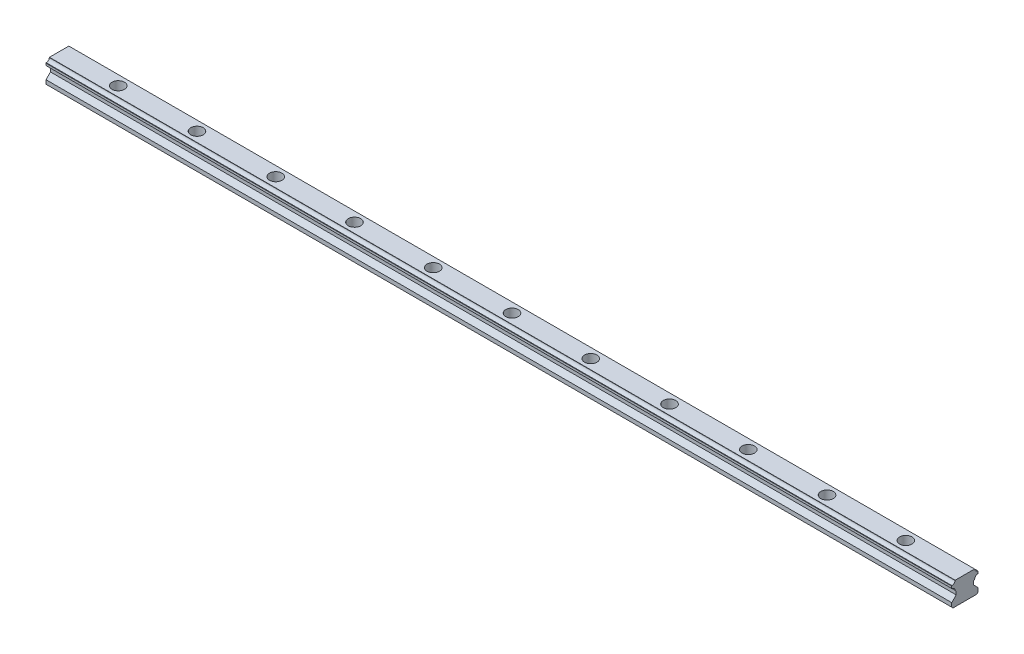
SolidWorks part; units mm, degrees
ref_plane "Спереди" through (0, 0, 0) normal (0, 0, 1) x (1, 0, 0)
ref_plane "Сверху" through (0, 0, 0) normal (0, 1, 0) x (1, 0, 0)
ref_plane "Сбоку" through (0, 0, 0) normal (1, 0, 0) x (0, 0, -1)
sketch "Эскиз1" plane through (0, 0, 0) normal (1, 0, 0) x (0, 0, -1)
  line L0 (-10, 0.9899) -> (-9.0101, 0)
  line L1 (-9.0101, 0) -> (9.0101, 0)
  line L2 (9.0101, 0) -> (10, 0.9899)
  line L3 (10, 0.9899) -> (10, 4)
  line L4 (10, 4) -> (6.6, 7.4)
  line L5 (6.6, 7.4) -> (6.6, 9.9)
  line L6 (6.6, 9.9) -> (7.5, 10.8)
  line L7 (9.8, 13.1) -> (10, 13.3)
  line L8 (10, 13.3) -> (10, 14.9)
  line L9 (10, 14.9) -> (9.8, 15.1)
  line L10 (7.5, 17.4) -> (7.4, 17.5)
  line L11 (7.4, 17.5) -> (-7.4, 17.5)
  line L12 (-7.4, 17.5) -> (-7.5, 17.4)
  line L13 (-9.8, 15.1) -> (-10, 14.9)
  line L14 (-10, 14.9) -> (-10, 13.3)
  line L15 (-10, 13.3) -> (-9.8, 13.1)
  line L16 (-7.5, 10.8) -> (-6.6, 9.9)
  line L17 (-6.6, 9.9) -> (-6.6, 7.4)
  line L18 (-6.6, 7.4) -> (-10, 4)
  line L19 (-10, 4) -> (-10, 0.9899)
  arc A0 (7.5, 10.8) -> (9.8, 13.1) centre (9.8, 10.8) cw
  arc A1 (9.8, 15.1) -> (7.5, 17.4) centre (9.8, 17.4) cw
  arc A2 (-7.5, 17.4) -> (-9.8, 15.1) centre (-9.8, 17.4) cw
  arc A3 (-9.8, 13.1) -> (-7.5, 10.8) centre (-9.8, 10.8) cw
  dimension "D1" = 20
  dimension "D2" = 17.5
extrude "Бобышка-Вытянуть1" add sketch "Эскиз1" against normal mid plane 690
hole_wizard "Цековка M6 для болта с шестигранной головкой класса А ГОСТ 78051" positions "Трехмерный эскиз1" profile "Эскиз4" counterbore size "M6" standard "ГОСТ"
sketch3d "Трехмерный эскиз1"
  line L5 (-345, 17.5, 0) -> (345, 17.5, 0) construction
  line L6 (-345, 17.5, -7.4) -> (-345, 17.5, 7.4) construction
  line L7 (345, 17.5, -7.4) -> (345, 17.5, 7.4) construction
  point P34 (0.3531, 17.5, 0)
  point P49 (0, 17.5, 0)
sketch "Эскиз4" plane through (0, 17.5, 0) normal (1, 0, 0) x (0, 0, 1)
  line L0 (0, 0) -> (0, 19.3016)
  line L1 (0, 19.3016) -> (3, 17.499)
  line L2 (3, 17.499) -> (3, 8.5)
  line L3 (3, 8.5) -> (4.75, 8.5)
  line L4 (4.75, 8.5) -> (4.75, 0)
  line L5 (4.75, 0) -> (0, 0)
  line L10 (0, 19.3016) -> (-3, 17.499) construction
  line L11 (0, -6.35) -> (0, 107.95) construction
  dimension "Диаметр отверстия" = 6
  dimension "Глубина отверстия" = 17.499
  dimension "Диаметр цековки" = 9.5
  dimension "Глубина цековки" = 8.5
  dimension "Угол заточки сверла" = 118
pattern_linear "Линейный массив1" count 6 spacing 60 along (1, 0, 0) of "Цековка M6 для болта с шестигранной головкой класса А ГОСТ 78051"
pattern_linear "Линейный массив2" count 6 spacing 60 along (-1, 0, 0) of "Цековка M6 для болта с шестигранной головкой класса А ГОСТ 78051"
